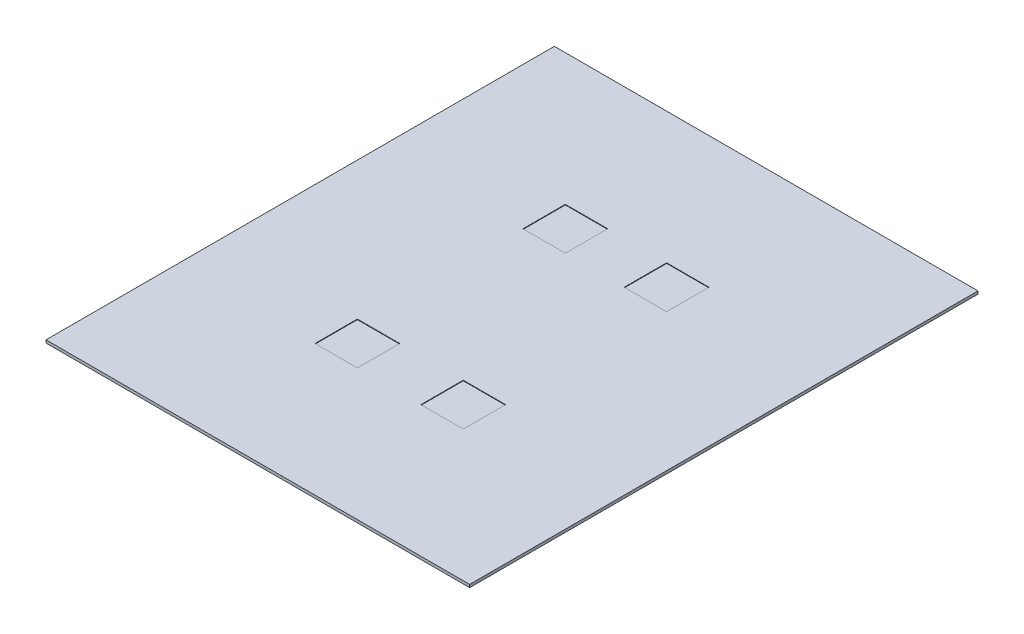
SolidWorks part; units mm, degrees
ref_plane "Front Plane" through (0, 0, 0) normal (0, 0, 1) x (1, 0, 0)
ref_plane "Top Plane" through (0, 0, 0) normal (0, 1, 0) x (1, 0, 0)
ref_plane "Right Plane" through (0, 0, 0) normal (1, 0, 0) x (0, 0, -1)
sketch "Sketch1" plane through (0, 0, 0) normal (0, 1, 0) x (1, 0, 0)
  line L1 (3750, -4500) -> (-3750, -4500)
  line L2 (3750, -4500) -> (3750, 4500)
  line L3 (3750, 4500) -> (-3750, 4500)
  line L4 (-3750, -4500) -> (-3750, 4500)
  line L5 (3750, -4500) -> (-3750, 4500) construction
  line L6 (3750, 4500) -> (-3750, -4500) construction
  point P0 (0, 0)
  dimension "D1" = 7500
  dimension "D2" = 9000
extrude "Boss-Extrude1" add sketch "Sketch1" along normal blind 50
sketch "Sketch2" plane through (0, 50, 0) normal (0, 1, 0) x (1, 0, 0)
  line L0 (-3750, 2700) -> (3750, 2700) construction
  line L1 (-3750, 4500) -> (-3750, -4500) construction
  line L2 (3750, -4500) -> (3750, 4500) construction
  line L3 (3750, 4500) -> (-3750, 4500) construction
  line L4 (3750, 900) -> (-3750, 900) construction
  line L5 (-3750, -4500) -> (3750, -4500) construction
  line L6 (-3750, -900) -> (0, -900) construction
  line L7 (0, 4500) -> (0, -4500) construction
  line L8 (3750, -2700) -> (1875, -2700) construction
  line L9 (-1875, 4500) -> (-1875, -4500) construction
  line L10 (1875, 4500) -> (1875, -4500) construction
  line L11 (0, 2700) -> (-1711.2131, 900) construction
  line L12 (0, -900) -> (-1875, -2700) construction
  line L13 (-480.6065, 1425) -> (-1230.6065, 1425)
  line L14 (-480.6065, 1425) -> (-480.6065, 2175)
  line L15 (-480.6065, 2175) -> (-1230.6065, 2175)
  line L16 (-1230.6065, 1425) -> (-1230.6065, 2175)
  line L17 (-480.6065, 1425) -> (-1230.6065, 2175) construction
  line L18 (-480.6065, 2175) -> (-1230.6065, 1425) construction
  line L19 (-1875, -2700) -> (0, -2700) construction
  line L20 (1875, -2700) -> (0, -900) construction
  line L21 (0, 2700) -> (1875, 900) construction
  line L23 (0, -2700) -> (-3750, -2700) construction
  line L28 (1875, -900) -> (3750, -900) construction
  line L29 (1312.5, 1425) -> (562.5, 1425)
  line L30 (-562.5, -2175) -> (-1312.5, -2175)
  line L31 (-562.5, -2175) -> (-562.5, -1425)
  line L32 (-562.5, -1425) -> (-1312.5, -1425)
  line L33 (-1312.5, -2175) -> (-1312.5, -1425)
  line L34 (-562.5, -2175) -> (-1312.5, -1425) construction
  line L35 (-562.5, -1425) -> (-1312.5, -2175) construction
  line L36 (1312.5, 1425) -> (1312.5, 2175)
  line L37 (1312.5, 2175) -> (562.5, 2175)
  line L38 (562.5, 1425) -> (562.5, 2175)
  line L39 (1312.5, 1425) -> (562.5, 2175) construction
  line L40 (1312.5, 2175) -> (562.5, 1425) construction
  line L41 (1312.5, -2175) -> (562.5, -2175)
  line L42 (1312.5, -2175) -> (1312.5, -1425)
  line L43 (1312.5, -1425) -> (562.5, -1425)
  line L44 (562.5, -2175) -> (562.5, -1425)
  line L45 (1312.5, -2175) -> (562.5, -1425) construction
  line L46 (1312.5, -1425) -> (562.5, -2175) construction
  point P24 (-855.6065, 1800)
  point P31 (900, 1800)
  point P35 (937.5, 1800)
  point P38 (-937.5, -1800)
  point P43 (900, -1800)
  point P46 (937.5, -1800)
  dimension "D1" = 1800
  dimension "D2" = 1800
  dimension "D3" = 1800
  dimension "D4" = 1800
  dimension "D5" = 1800
  dimension "D6" = 750
  dimension "D7" = 750
  dimension "D8" = 1875
  dimension "D9" = 750
  dimension "D10" = 750
  dimension "D11" = 750
  dimension "D12" = 750
  dimension "D13" = 750
  dimension "D14" = 1875
  dimension "D15" = 1875
  dimension "D16" = 750
extrude "Cut-Extrude1" cut sketch "Sketch2" against normal blind 10
